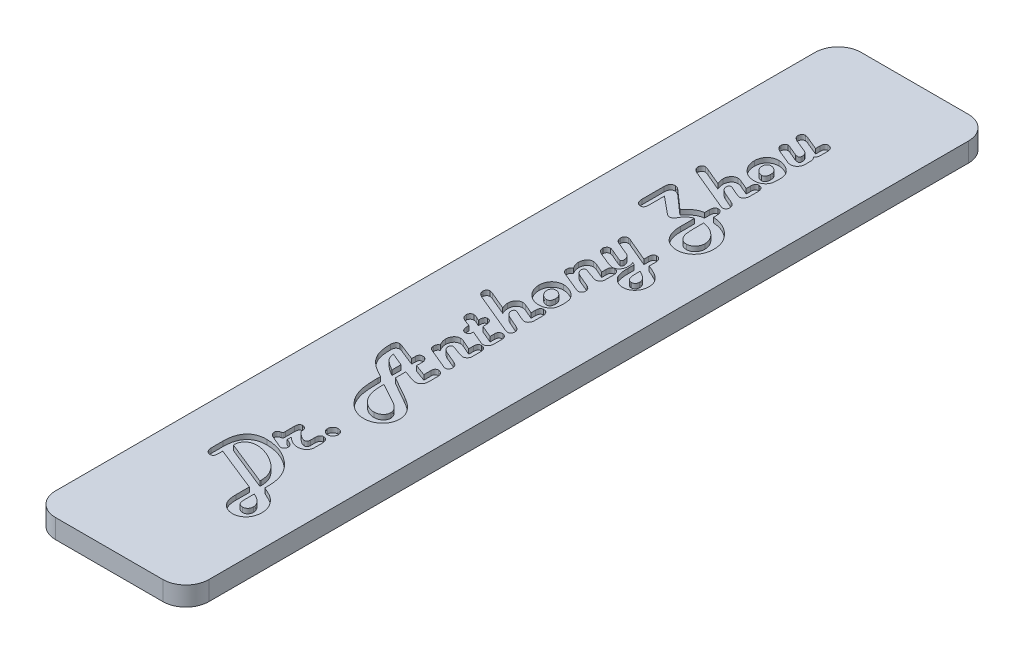
SolidWorks part; units mm, degrees
ref_plane "Front Plane" through (0, 0, 0) normal (0, 0, 1) x (1, 0, 0)
ref_plane "Top Plane" through (0, 0, 0) normal (0, 1, 0) x (1, 0, 0)
ref_plane "Right Plane" through (0, 0, 0) normal (1, 0, 0) x (0, 0, -1)
sketch "Sketch1" plane through (0, 0, 0) normal (0, 0, 1) x (1, 0, 0)
  line L0 (0, 1.5875) -> (0, -1.5875)
  line L1 (-12.7, 0) -> (12.7, 0) construction
  point P6 (0, 0)
  dimension "Width" = 25.4
  dimension "Thk" = 3.175
sketch "Sketch2" plane through (0, 0, 0) normal (1, 0, 0) x (0, 0, -1)
  line L0 (66.675, 0) -> (-66.675, 0)
  point P4 (0, 0)
  dimension "Length" = 133.35
sketch "Sketch3" plane through (0, 0, 0) normal (0, 0, 1) x (1, 0, 0)
  line L1 (12.7, 1.5875) -> (-12.7, 1.5875)
  line L2 (12.7, 1.5875) -> (12.7, -1.5875)
  line L3 (12.7, -1.5875) -> (-12.7, -1.5875)
  line L4 (-12.7, 1.5875) -> (-12.7, -1.5875)
  line L5 (12.7, 1.5875) -> (-12.7, -1.5875) construction
  line L6 (12.7, -1.5875) -> (-12.7, 1.5875) construction
  point P0 (0, 0)
extrude "Boss-Extrude1" add sketch "Sketch3" along normal up to vertex (66.675 mm away) and the other way up to vertex (66.675 mm away) up to point (0, 0, 66.675) other way up to point (0, 0, -66.675)
sketch "Sketch5" plane through (0, 1.5875, 0) normal (0, 1, 0) x (1, 0, 0)
  line L2 (9.652, -66.675) -> (-9.398, -66.675) construction
  line L3 (-12.7, -63.5025) -> (-12.7, 63.627) construction
  line L12 (12.7, -66.675) -> (12.7, 66.675)
  line L13 (12.7, 66.675) -> (-12.7, 66.675)
  line L14 (-12.7, 66.675) -> (-12.7, -66.675)
  line L15 (-12.7, -66.675) -> (12.7, -66.675)
  line L16 (12.7, -62.865) -> (12.7, 62.865)
  line L17 (8.89, 66.675) -> (-8.89, 66.675)
  line L18 (-12.7, 62.865) -> (-12.7, -62.865)
  line L19 (-8.89, -66.675) -> (8.89, -66.675)
  arc A8 (12.7, 62.865) -> (8.89, 66.675) centre (8.89, 62.865) ccw
  arc A9 (-8.89, 66.675) -> (-12.7, 62.865) centre (-8.89, 62.865) ccw
  arc A10 (12.7, -62.865) -> (8.89, -66.675) centre (8.89, -62.865) cw
  arc A11 (-8.89, -66.675) -> (-12.7, -62.865) centre (-8.89, -62.865) cw
  dimension "D2" = 3.81
  dimension "D1" = 0
extrude "Cut-Extrude2" cut sketch "Sketch5" against normal through all flip side to cut
sketch "Sketch4" plane through (0, 1.5875, 0) normal (0, 1, 0) x (1, 0, 0)
  line L0 (0, 0) -> (2.54, 0) construction
  line L1 (2.54, -66.675) -> (2.54, 66.675) construction
  line L2 (8.89, 66.675) -> (-8.89, 66.675) construction
  text T0 "Dr. Anthony Zhou" font "Harlow Solid Italic" height in points 28
  point P8 (2.54, 0)
  dimension "D1" = 2.54
extrude "Cut-Extrude1" cut sketch "Sketch4" against normal blind 0.7937
